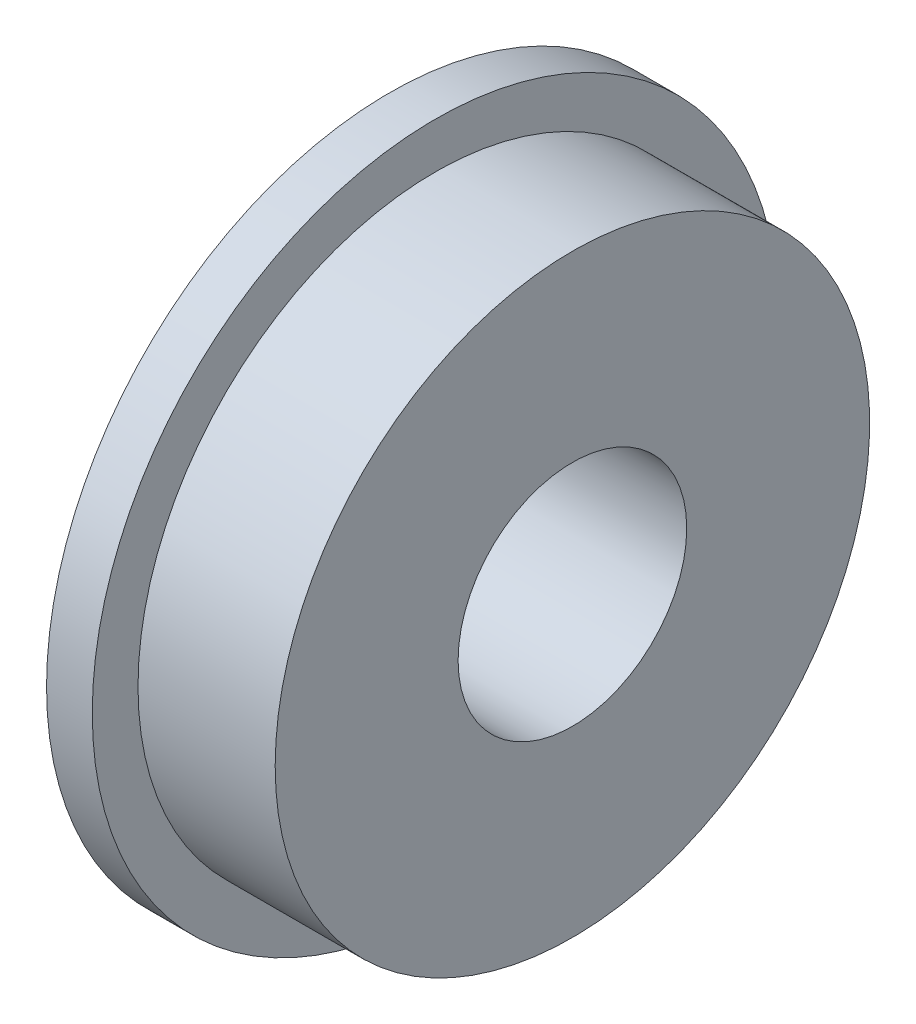
SolidWorks part; units mm, degrees
ref_plane "Front" through (0, 0, 0) normal (0, 0, 1) x (1, 0, 0)
ref_plane "Top" through (0, 0, 0) normal (0, 1, 0) x (1, 0, 0)
ref_plane "Right" through (0, 0, 0) normal (1, 0, 0) x (0, 0, -1)
sketch "Sketch1" plane through (0, 0, 0) normal (0, 1, 0) x (1, 0, 0)
  line L0 (0, 0) -> (4, 0) construction
  line L1 (4, 2.5) -> (0, 2.5)
  line L2 (0, 2.5) -> (0, 7.5)
  line L3 (0, 7.5) -> (1, 7.5)
  line L4 (1, 7.5) -> (1, 6.5)
  line L5 (1, 6.5) -> (4, 6.5)
  line L6 (4, 6.5) -> (4, 2.5)
  point P9 (0, 0)
  dimension "D1" = 5
  dimension "D2" = 1
  dimension "D3" = 4
  dimension "D4" = 15
  dimension "D5" = 13
revolve "Revolve1" add sketch "Sketch1" angle 360 about L0
